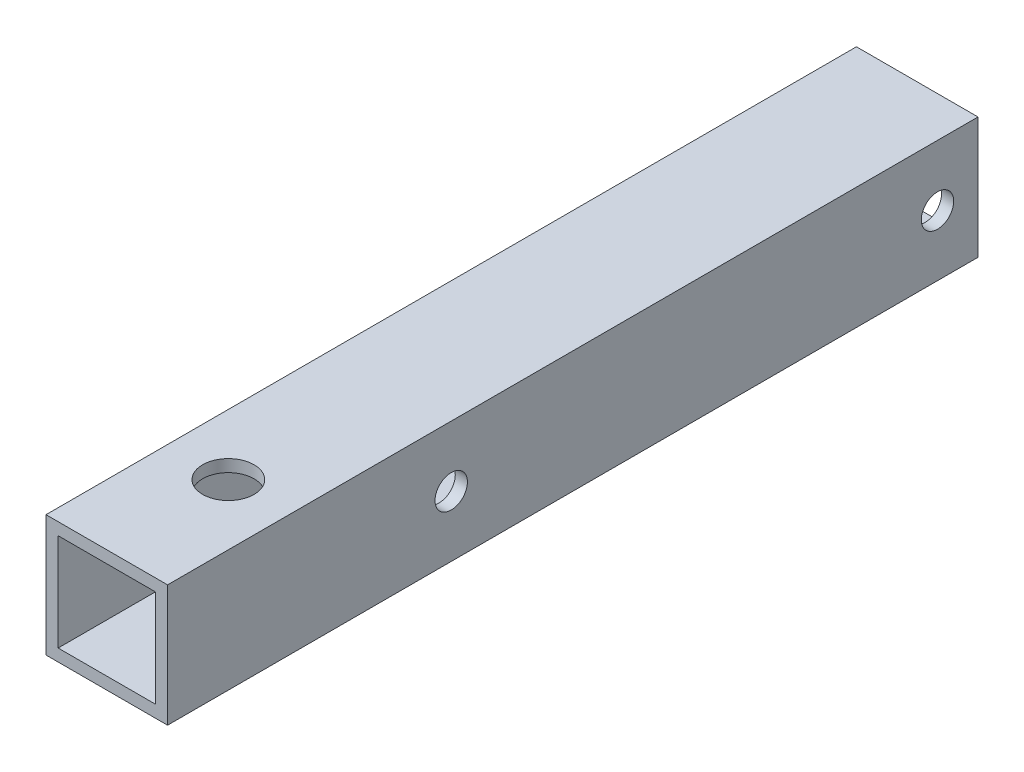
SolidWorks part; units mm, degrees
material "5052-H34"
ref_plane "正面" through (0, 0, 0) normal (0, 0, 1) x (1, 0, 0)
ref_plane "平面" through (0, 0, 0) normal (0, 1, 0) x (1, 0, 0)
ref_plane "右側面" through (0, 0, 0) normal (1, 0, 0) x (0, 0, -1)
sketch "ｽｹｯﾁ1" plane through (0, 0, 0) normal (0, 0, 1) x (1, 0, 0)
  line L1 (-7.5, 7.5) -> (7.5, 7.5)
  line L2 (-7.5, 7.5) -> (-7.5, -7.5)
  line L3 (-7.5, -7.5) -> (7.5, -7.5)
  line L4 (7.5, 7.5) -> (7.5, -7.5)
  line L5 (-7.5, 7.5) -> (7.5, -7.5) construction
  line L6 (-7.5, -7.5) -> (7.5, 7.5) construction
  point P0 (0, 0)
  dimension "D1" = 15
  dimension "D2" = 15
extrude "押し出し-薄板1" add sketch "ｽｹｯﾁ1" along normal blind 100 thin
sketch "ｽｹｯﾁ2" plane through (7.5, 0, 0) normal (1, 0, 0) x (0, 0, -1)
  line L0 (0, 0) -> (-65, 0) construction
  line L1 (0, -7.5) -> (0, 7.5) construction
  circle A0 centre (-5, 0) radius 2
  circle A1 centre (-65, 0) radius 2
  dimension "D1" = 4
  dimension "D2" = 5
  dimension "D3" = 60
extrude "ｶｯﾄ - 押し出し1" cut sketch "ｽｹｯﾁ2" against normal through all
sketch "ｽｹｯﾁ3" plane through (0, 7.5, 0) normal (0, 1, 0) x (1, 0, 0)
  line L0 (0, -100) -> (0, -85) construction
  line L1 (7.5, -100) -> (-7.5, -100) construction
  circle A0 centre (0, -85) radius 3.175
  dimension "D1" = 6.35
  dimension "D2" = 15
extrude "ｶｯﾄ - 押し出し2" cut sketch "ｽｹｯﾁ3" against normal through all
